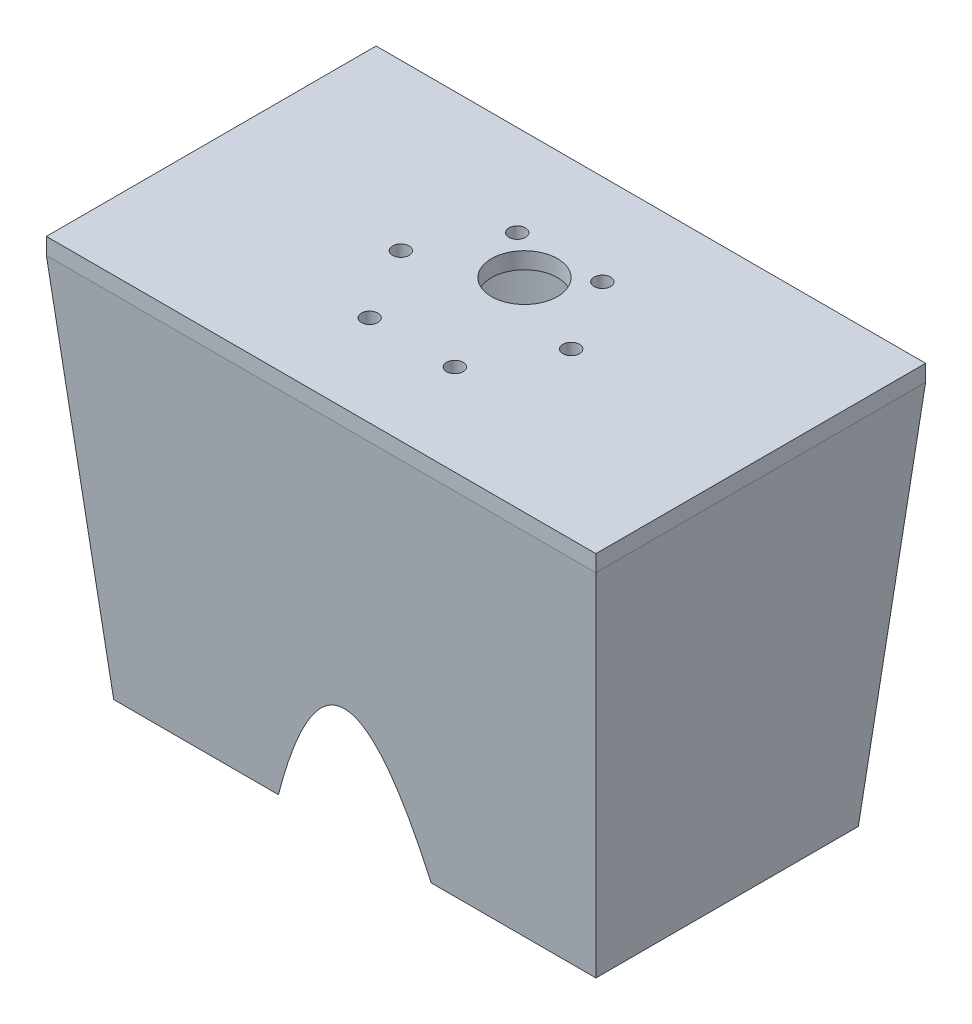
SolidWorks part; units mm, degrees
ref_plane "Alzado" through (0, 0, 0) normal (0, 0, 1) x (1, 0, 0)
ref_plane "Planta" through (0, 0, 0) normal (0, 1, 0) x (1, 0, 0)
ref_plane "Vista lateral" through (0, 0, 0) normal (1, 0, 0) x (0, 0, -1)
sketch "Croquis1" plane through (0, 0, 0) normal (0, 1, 0) x (1, 0, 0)
  line L1 (-50, -30) -> (50, -30)
  line L2 (-50, -30) -> (-50, 30)
  line L3 (-50, 30) -> (50, 30)
  line L4 (50, -30) -> (50, 30)
  line L5 (-50, -30) -> (50, 30) construction
  line L6 (-50, 30) -> (50, -30) construction
  circle A0 centre (0, 0) radius 18.5 construction
  circle A1 centre (0, 7) radius 6
  circle A2 centre (15.5, 0) radius 1.5
  circle A3 centre (7.75, -13.4234) radius 1.5
  circle A4 centre (-7.75, -13.4234) radius 1.5
  circle A5 centre (-15.5, 0) radius 1.5
  circle A6 centre (-7.75, 13.4234) radius 1.5
  circle A7 centre (7.75, 13.4234) radius 1.5
  point P20 (0, 0)
  dimension "D1" = 37
  dimension "D2" = 12
  dimension "D4" = 3
  dimension "D3" = 7
  dimension "D5" = 15.5
  dimension "D7" = 100
  dimension "D8" = 60
  dimension "D6" = 6
extrude "Saliente-Extruir1" add sketch "Croquis1" along normal blind 3
sketch "Croquis2" plane through (0, 0, 0) normal (0, 1, 0) x (1, 0, 0)
  circle A0 centre (0, 0) radius 18.5
  circle A1 centre (0, 0) radius 21.5
  dimension "D1" = 37
  dimension "D2" = 3
extrude "Saliente-Extruir2" add sketch "Croquis2" against normal blind 20
sketch "Croquis4" plane through (0, 0, 0) normal (0, -1, 0) x (1, 0, 0)
  line L1 (-50, -30) -> (50, -30)
  line L2 (-50, -30) -> (-50, 30)
  line L3 (-50, 30) -> (50, 30)
  line L4 (50, -30) -> (50, 30)
  line L5 (-50, -30) -> (50, 30) construction
  line L6 (-50, 30) -> (50, -30) construction
  circle A0 centre (0, 0) radius 21.5
  point P0 (0, 0)
  dimension "D3" = 43
  dimension "D1" = 60
  dimension "D2" = 100
extrude "Saliente-Extruir3" add sketch "Croquis4" along normal blind 70 draft 5
